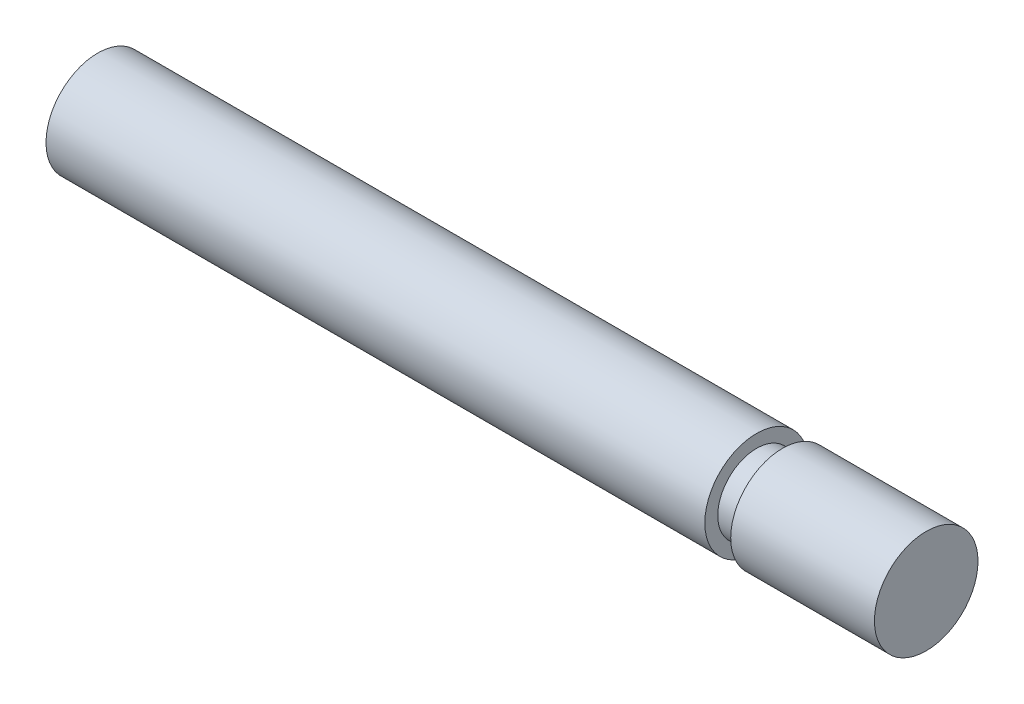
SolidWorks part; units mm, degrees
ref_plane "Front Plane" through (0, 0, 0) normal (0, 0, 1) x (1, 0, 0)
ref_plane "Top Plane" through (0, 0, 0) normal (0, 1, 0) x (1, 0, 0)
ref_plane "Right Plane" through (0, 0, 0) normal (1, 0, 0) x (0, 0, -1)
sketch "Sketch3" plane through (0, 0, 0) normal (0, 0, 1) x (1, 0, 0)
  line L0 (0, 0) -> (0, 50)
  line L1 (0, 0) -> (700, 0)
  line L2 (700, 0) -> (700, 50)
  line L3 (700, 50) -> (661.2, 50)
  line L4 (661.2, 50) -> (661.2, 37.5)
  line L5 (661.2, 37.5) -> (636.2, 37.5)
  line L6 (636.2, 37.5) -> (636.2, 50)
  line L7 (636.2, 50) -> (2.6762, 50)
  line L8 (2.6762, 50) -> (0, 50)
  dimension "D1" = 50
  dimension "D2" = 38.8
  dimension "D3" = 12.5
  dimension "D4" = 25
revolve "Revolve1" add sketch "Sketch3" angle 360 about L1
sketch "Sketch4" plane through (700, 0, 0) normal (1, 0, 0) x (0, 0, -1)
  circle A0 centre (0, 0) radius 50
extrude "Boss-Extrude1" add sketch "Sketch4" along normal blind 100
